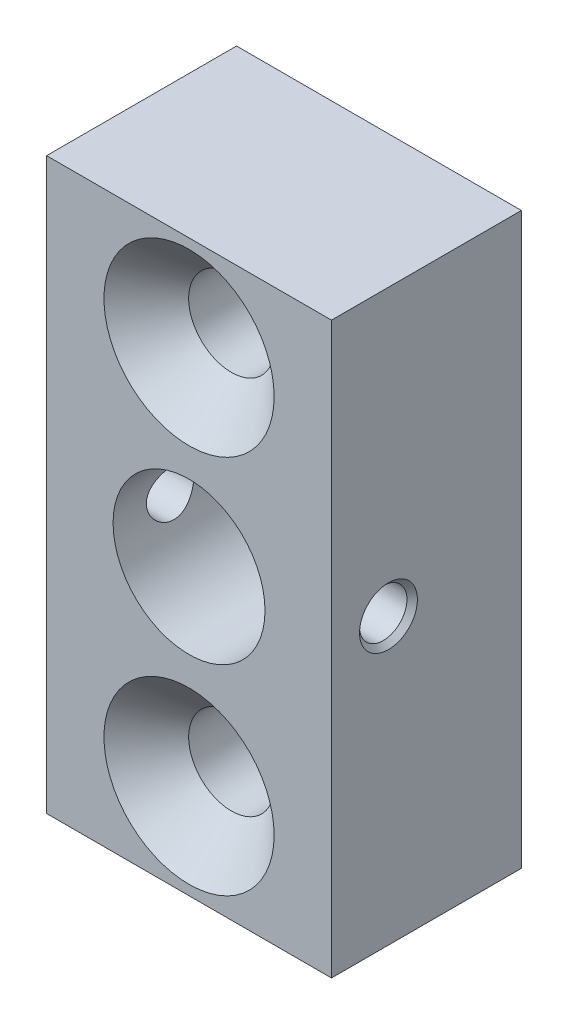
SolidWorks part; units mm, degrees
material "1.0037 (S235JR)"
ref_plane "Ebene vorne" through (0, 0, 0) normal (0, 0, 1) x (1, 0, 0)
ref_plane "Ebene oben" through (0, 0, 0) normal (0, 1, 0) x (1, 0, 0)
ref_plane "Ebene rechts" through (0, 0, 0) normal (1, 0, 0) x (0, 0, -1)
sketch "Skizze1" plane through (0, 0, 0) normal (0, 0, 1) x (1, 0, 0)
  line L1 (0, 0) -> (15, 0)
  line L2 (0, 0) -> (0, 30)
  line L3 (0, 30) -> (15, 30)
  line L4 (15, 0) -> (15, 30)
  dimension "D1" = 15
  dimension "D2" = 30
extrude "Aufsatz-Linear austragen1" add sketch "Skizze1" along normal blind 10
hole_wizard "Formsenkung für M4 SFHCS1" positions "Skizze2" profile "Skizze3" countersink size "M4" standard "ANSI Metrisch" end condition through all
sketch "Skizze2" plane through (0, 0, 10) normal (0, 0, 1) x (1, 0, 0)
  line L0 (7.5, 30) -> (7.5, 0) construction
  line L1 (15, 30) -> (0, 30) construction
  line L2 (0, 0) -> (15, 0) construction
  point P0 (7.5, 25)
  point P2 (7.5, 5)
  dimension "D1" = 20
  dimension "D2" = 5
sketch "Skizze3" plane through (7.5, 25, 10) normal (1, 0, 0) x (0, -1, 0)
  line L0 (0, 0) -> (0, 10)
  line L1 (0, 10) -> (2.25, 10)
  line L2 (2.25, 10) -> (2.25, 2.23)
  line L3 (2.25, 2.23) -> (4.48, 0)
  line L5 (4.48, 0) -> (0, 0)
  line L6 (-2.25, 2.23) -> (-4.48, 0) construction
  line L11 (0, -6.35) -> (0, 107.95) construction
  dimension "Bohrerdurchmesser" = 4.5
  dimension "Bohrungstiefe" = 10
  dimension "Senkdurchmesser (Oben)" = 8.96
  dimension "Senkwinkel (Oben)" = 90
sketch "Skizze4" plane through (0, 0, 0) normal (0, 0, -1) x (-1, 0, 0)
  line L0 (-7.5, 30) -> (-7.5, 0) construction
  line L1 (-15, 30) -> (0, 30) construction
  line L2 (0, 0) -> (-15, 0) construction
  circle A0 centre (-7.5, 25) radius 3.1
  circle A1 centre (-7.5, 5) radius 3.1
  dimension "D1" = 6.2
  dimension "D2" = 6.2
extrude "Schnitt-Linear austragen1" cut sketch "Skizze4" against normal blind 4
sketch "Skizze7" plane through (0, 0, 10) normal (0, 0, 1) x (1, 0, 0)
  line L0 (0, 30) -> (15, 0) construction
  circle A0 centre (7.5, 15) radius 4
  dimension "D1" = 8
extrude "Schnitt-Linear austragen2" cut sketch "Skizze7" against normal blind 6
hole_wizard "M3x0.5 Gewindebohrung1" positions "Skizze10" profile "Skizze9" tap size "M3x0.5" standard "ANSI Metrisch" end condition through all
sketch "Skizze10" plane through (15, 0, 0) normal (1, 0, 0) x (0, 0, -1)
  line L0 (-7, 30) -> (-7, 0) construction
  line L1 (-10, 30) -> (0, 30) construction
  line L2 (-10, 0) -> (0, 0) construction
  line L4 (0, 15) -> (-10, 15) construction
  line L5 (0, 0) -> (0, 30) construction
  line L6 (-10, 0) -> (-10, 30) construction
  point P0 (-7, 15)
  dimension "D1" = 3
cosmetic thread "Bohrungsgewinde1" parameters "D2"=3
sketch "Skizze9" plane through (15, 15, 7) normal (0, 1, 0) x (0, 0, -1)
  line L0 (0, 0) -> (0, 15)
  line L1 (0, 15) -> (1.25, 15)
  line L2 (1.25, 15) -> (1.25, 0.275)
  line L3 (1.25, 0.275) -> (1.525, 0)
  line L5 (1.525, 0) -> (0, 0)
  line L6 (-1.25, 0.275) -> (-1.525, 0) construction
  line L11 (0, -6.35) -> (0, 107.95) construction
  dimension "Bohrerdurchmesser" = 2.5
  dimension "Bohrungstiefe" = 15
  dimension "Senkdurchmesser (Oben)" = 3.05
  dimension "Senkwinkel (Oben)" = 90
